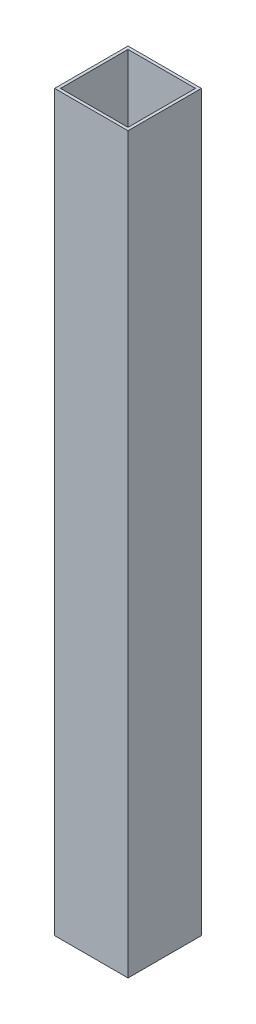
SolidWorks part; units mm, degrees
ref_plane "Front Plane" through (0, 0, 0) normal (0, 0, 1) x (1, 0, 0)
ref_plane "Top Plane" through (0, 0, 0) normal (0, 1, 0) x (1, 0, 0)
ref_plane "Right Plane" through (0, 0, 0) normal (1, 0, 0) x (0, 0, -1)
sketch "Sketch1" plane through (0, 0, 0) normal (0, 1, 0) x (1, 0, 0)
  line L0 (-23, 23) -> (23, 23)
  line L1 (-25, -25) -> (25, -25)
  line L2 (-25, -25) -> (-25, 25)
  line L3 (-25, 25) -> (25, 25)
  line L4 (25, -25) -> (25, 25)
  line L5 (-25, -25) -> (25, 25) construction
  line L6 (-25, 25) -> (25, -25) construction
  line L7 (23, -23) -> (23, 23)
  line L8 (-23, -23) -> (23, -23)
  line L9 (-23, -23) -> (-23, 23)
  point P0 (0, 0)
  dimension "D1" = 50
  dimension "D2" = 2
extrude "Boss-Extrude1" add sketch "Sketch1" along normal blind 500
